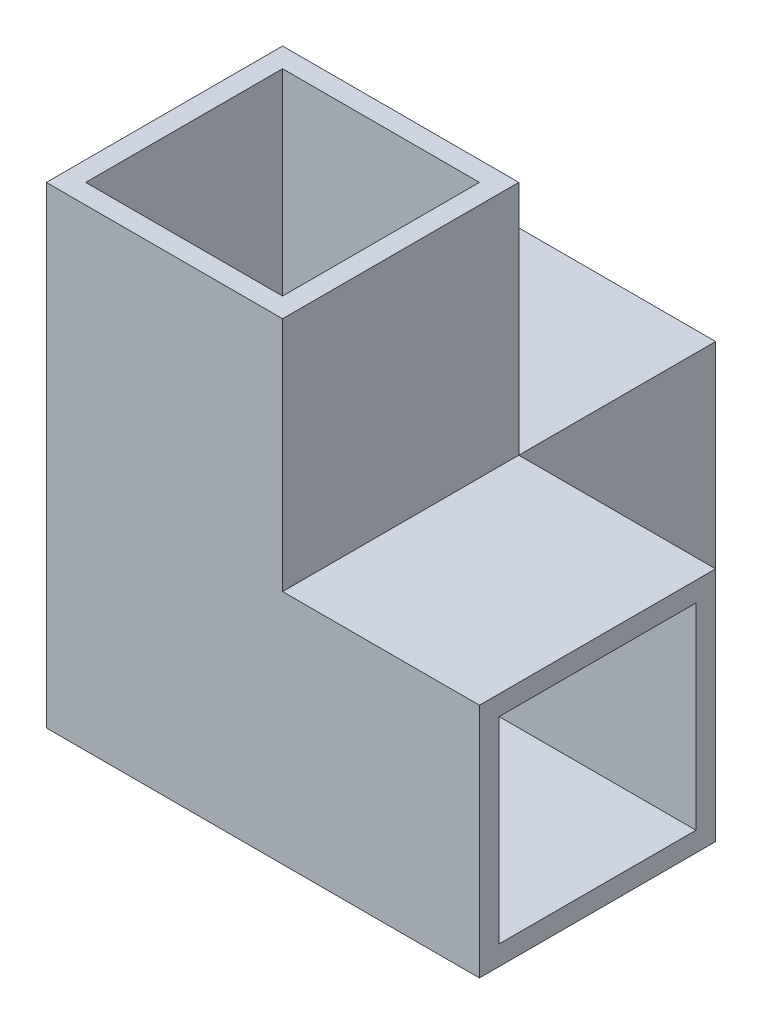
SolidWorks part; units mm, degrees
ref_plane "前视基准面" through (0, 0, 0) normal (0, 0, 1) x (1, 0, 0)
ref_plane "上视基准面" through (0, 0, 0) normal (0, 1, 0) x (1, 0, 0)
ref_plane "右视基准面" through (0, 0, 0) normal (1, 0, 0) x (0, 0, -1)
sketch "草图1" plane through (0, 0, 0) normal (0, 1, 0) x (1, 0, 0)
  line L0 (-104.9562, 0) -> (151.1105, 0) construction
  line L1 (0, 88) -> (0, 0)
  line L2 (0, -69.3713) -> (0, 109.6388) construction
  line L3 (0, 0) -> (88, 0)
  line L4 (0, 88) -> (48, 88)
  line L5 (48, 88) -> (48, 48)
  line L6 (48, 48) -> (88, 48)
  line L7 (88, 48) -> (88, 0)
extrude "凸台-拉伸1" add sketch "草图1" along normal blind 48
sketch "草图2" plane through (0, 48, 0) normal (0, 1, 0) x (1, 0, 0)
  line L1 (48, 48) -> (0, 48)
  line L2 (48, 48) -> (48, 0)
  line L3 (48, 0) -> (0, 0)
  line L4 (0, 48) -> (0, 0)
extrude "凸台-拉伸2" add sketch "草图2" along normal blind 48
sketch "草图3" plane through (88, 0, 0) normal (1, 0, 0) x (0, 0, -1)
  line L0 (0, 48) -> (48, 48) construction
  line L1 (44, 44) -> (4, 44)
  line L2 (44, 44) -> (44, 4)
  line L3 (44, 4) -> (4, 4)
  line L4 (4, 44) -> (4, 4)
  line L5 (0, 48) -> (0, 0) construction
  line L6 (0, 0) -> (48, 0) construction
  line L7 (48, 48) -> (48, 0) construction
  dimension "D1" = 4
  dimension "D2" = 4
  dimension "D3" = 4
  dimension "D4" = 4
extrude "切除-拉伸1" cut sketch "草图3" against normal blind 84
sketch "草图4" plane through (0, 0, -88) normal (0, 0, -1) x (-1, 0, 0)
  line L0 (-4, 44) -> (-44, 44)
  line L1 (-4, 44) -> (-4, 4)
  line L2 (-4, 4) -> (-44, 4)
  line L3 (-44, 44) -> (-44, 4)
  line L4 (-48, 48) -> (0, 48) construction
  line L5 (-48, 48) -> (-48, 0) construction
  dimension "D1" = 4
  dimension "D2" = 4
extrude "切除-拉伸2" cut sketch "草图4" against normal blind 84
sketch "草图5" plane through (0, 96, 0) normal (0, 1, 0) x (1, 0, 0)
  line L0 (44, 44) -> (4, 44)
  line L1 (44, 44) -> (44, 4)
  line L2 (44, 4) -> (4, 4)
  line L3 (4, 44) -> (4, 4)
  line L4 (48, 48) -> (0, 48) construction
  line L5 (0, 48) -> (0, 0) construction
  dimension "D1" = 4
  dimension "D2" = 4
extrude "切除-拉伸3" cut sketch "草图5" against normal blind 84
sketch "草图6" plane through (4, 0, 0) normal (1, 0, 0) x (0, 0, -1)
  line L5 (0, 48) -> (48, 48)
  line L6 (0, 48) -> (0, 0)
  line L7 (0, 0) -> (48, 0)
  line L8 (48, 48) -> (48, 0)
extrude "凸台-拉伸5" add sketch "草图6" along normal blind 44 contours L5 L8 L7 L6
